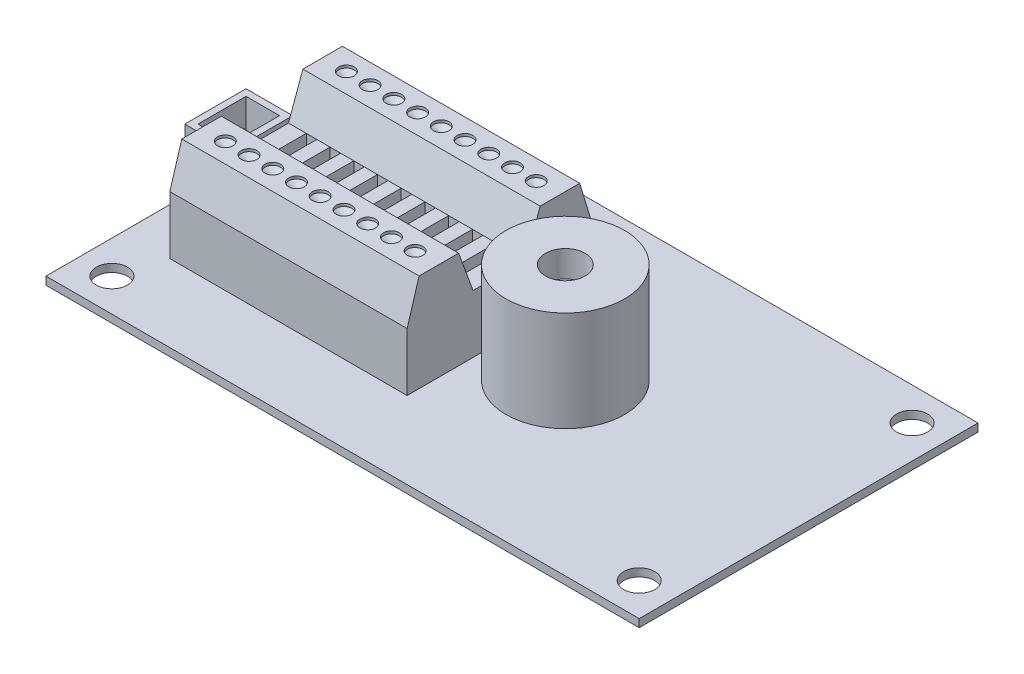
SolidWorks part; units mm, degrees
ref_plane "Front Plane" through (0, 0, 0) normal (0, 0, 1) x (1, 0, 0)
ref_plane "Top Plane" through (0, 0, 0) normal (0, 1, 0) x (1, 0, 0)
ref_plane "Right Plane" through (0, 0, 0) normal (1, 0, 0) x (0, 0, -1)
sketch "Sketch1" plane through (0, 0, 0) normal (0, 1, 0) x (1, 0, 0)
  line L1 (-28.575, 16.3195) -> (28.575, 16.3195)
  line L2 (-28.575, 16.3195) -> (-28.575, -16.3195)
  line L3 (-28.575, -16.3195) -> (28.575, -16.3195)
  line L4 (28.575, 16.3195) -> (28.575, -16.3195)
  line L5 (-28.575, 16.3195) -> (28.575, -16.3195) construction
  line L6 (-28.575, -16.3195) -> (28.575, 16.3195) construction
  point P0 (0, 0)
  dimension "D1" = 32.639
  dimension "D2" = 57.15
extrude "Boss-Extrude1" add sketch "Sketch1" along normal blind 0.762
hole_wizard "Ø3.0mm Dowel Hole1" positions "Sketch2" profile "Sketch3" hole size "Ø3.0" standard "ANSI Metric" end condition through all
sketch "Sketch2" plane through (0, 0.762, 0) normal (0, 1, 0) x (1, 0, 0)
  line L0 (28.575, 16.3195) -> (-28.575, 16.3195) construction
  line L1 (-28.575, 16.3195) -> (-28.575, -16.3195) construction
  line L2 (28.575, -16.3195) -> (28.575, 16.3195) construction
  line L3 (-28.575, -16.3195) -> (28.575, -16.3195) construction
  point P0 (-25.4, 13.1445)
  point P2 (-25.4, -13.1445)
  point P4 (25.4, -13.1445)
  point P6 (25.4, 13.1445)
  point P13 (0, 0)
  dimension "D1" = 3.175
  dimension "D2" = 3.175
  dimension "D3" = 3.175
  dimension "D4" = 3.175
sketch "Sketch3" plane through (-25.4, 0.762, -13.1445) normal (1, 0, 0) x (0, 0, 1)
  line L0 (0, 0) -> (0, 0.762)
  line L1 (0, 0.762) -> (1.5, 0.762)
  line L2 (1.5, 0.762) -> (1.5, 0)
  line L5 (1.5, 0) -> (0, 0)
  line L11 (0, -6.35) -> (0, 107.95) construction
  dimension "Thru Hole Dia." = 3
  dimension "Thru Hole Depth" = 0.762
sketch "Sketch5" plane through (0, 0.762, 0) normal (0, 1, 0) x (1, 0, 0)
  line L0 (-28.575, 16.3195) -> (-28.575, -16.3195) construction
  line L1 (-28.575, 2.95) -> (-24.075, 2.95)
  line L2 (-28.575, 2.95) -> (-28.575, -2.95)
  line L3 (-28.575, -2.95) -> (-24.075, -2.95)
  line L4 (-24.075, 2.95) -> (-24.075, -2.95)
  line L5 (-28.575, 2.95) -> (-24.075, -2.95) construction
  line L6 (-28.575, -2.95) -> (-24.075, 2.95) construction
  point P0 (-26.325, 0)
  point P7 (0, 0)
  dimension "D1" = 5.9
  dimension "D2" = 4.5
  dimension "D3" = 0
extrude "Boss-Extrude2" add sketch "Sketch5" along normal blind 6
sketch "Sketch6" plane through (0, 6.762, 0) normal (0, 1, 0) x (1, 0, 0)
  line L0 (-24.075, 2.95) -> (-28.575, 2.95) construction
  line L1 (-27.94, 2.315) -> (-24.71, 2.315)
  line L2 (-27.94, 2.315) -> (-27.94, -2.315)
  line L3 (-27.94, -2.315) -> (-24.71, -2.315)
  line L4 (-24.71, 2.315) -> (-24.71, -2.315)
  line L5 (-27.94, 2.315) -> (-24.71, -2.315) construction
  line L6 (-27.94, -2.315) -> (-24.71, 2.315) construction
  line L7 (-28.575, -2.95) -> (-24.075, -2.95) construction
  line L8 (-24.075, -2.95) -> (-24.075, 2.95) construction
  line L9 (-28.575, 2.95) -> (-28.575, -2.95) construction
  point P0 (-26.325, 0)
  dimension "D1" = 0.635
  dimension "D2" = 0.635
  dimension "D3" = 0.635
  dimension "D4" = 0.635
extrude "Cut-Extrude1" cut sketch "Sketch6" against normal blind 5.08
sketch "Sketch7" plane through (0, 1.682, 0) normal (0, 1, 0) x (1, 0, 0)
  line L0 (-28.575, 2.95) -> (-28.575, -2.95) construction
  line L3 (-24.075, 2.95) -> (-28.575, 2.95) construction
  line L4 (-28.575, -2.95) -> (-24.075, -2.95) construction
  circle A0 centre (-26.875, 1) radius 0.25
  circle A1 centre (-26.875, -1) radius 0.25
  point P8 (0, 0)
  point P11 (0, 0)
  dimension "D1" = 0.5
  dimension "D2" = 0.5
  dimension "D3" = 2
  dimension "D5" = 1.95
  dimension "D6" = 1.95
  dimension "D4" = 1.7
extrude "Boss-Extrude3" add sketch "Sketch7" along normal blind 3.4
ref_plane "Plane1" through (-24.075, 0, 0) normal (1, 0, 0) x (0, 0, -1)
sketch "Sketch9" plane through (-24.075, 0, 0) normal (1, 0, 0) x (0, 0, -1)
  line L0 (0, 0) -> (0, 6.35)
  line L1 (0, 6.35) -> (2.54, 6.35)
  line L2 (2.54, 6.35) -> (3.9267, 10.16)
  line L3 (3.9267, 10.16) -> (7.7367, 10.16)
  line L4 (7.7367, 10.16) -> (8.89, 6.35)
  line L5 (8.89, 6.35) -> (8.89, 0)
  line L6 (8.89, 0) -> (0, 0)
  dimension "D1" = 10.16
  dimension "D2" = 3.81
  dimension "D3" = 8.89
  dimension "D4" = 6.35
  dimension "D5" = 110
  dimension "D6" = 2.54
extrude "Boss-Extrude4" add sketch "Sketch9" along normal blind 22.86
hole_wizard "Ø1.5mm Dowel Hole1" positions "Sketch12" profile "Sketch11" hole size "Ø1.5" standard "ANSI Metric"
sketch "Sketch12" plane through (0, 10.16, 0) normal (0, 1, 0) x (1, 0, 0)
  line L0 (-24.075, 8.89) -> (-24.075, 2.95) construction
  line L1 (-1.215, 7.7367) -> (-24.075, 7.7367) construction
  point P0 (-21.789, 5.8317)
  point P2 (-19.503, 5.8317)
  point P4 (-17.217, 5.8317)
  point P6 (-14.931, 5.8317)
  point P8 (-12.645, 5.8317)
  point P10 (-10.359, 5.8317)
  point P12 (-8.073, 5.8317)
  point P14 (-5.787, 5.8317)
  point P16 (-3.501, 5.8317)
  point P21 (0, 0)
  dimension "D1" = 2.286
  dimension "D2" = 2.286
  dimension "D3" = 2.286
  dimension "D4" = 2.286
  dimension "D5" = 2.286
  dimension "D6" = 2.286
  dimension "D7" = 2.286
  dimension "D8" = 2.286
  dimension "D9" = 2.286
  dimension "D10" = 1.905
sketch "Sketch11" plane through (-21.789, 10.16, -5.8317) normal (1, 0, 0) x (0, 0, 1)
  line L0 (0, 0) -> (0, 0.7046)
  line L1 (0, 0.7046) -> (0.75, 0.254)
  line L2 (0.75, 0.254) -> (0.75, 0)
  line L5 (0.75, 0) -> (0, 0)
  line L10 (0, 0.7046) -> (-0.75, 0.254) construction
  line L11 (0, -6.35) -> (0, 107.95) construction
  dimension "Hole Dia." = 1.5
  dimension "Hole Depth" = 0.254
  dimension "Drill Angle" = 118
sketch "Sketch13" plane through (0, 6.35, 0) normal (0, 1, 0) x (1, 0, 0)
  line L0 (-1.215, 2.54) -> (-24.075, 2.54) construction
  line L1 (-22.3558, 2.54) -> (-21.3398, 2.54)
  line L2 (-22.3558, 2.54) -> (-22.3558, 0)
  line L3 (-22.3558, 0) -> (-21.3398, 0)
  line L4 (-21.3398, 2.54) -> (-21.3398, 0)
  line L5 (-1.215, 0) -> (-24.075, 0) construction
  dimension "D1" = 1.016
extrude "Cut-Extrude2" cut sketch "Sketch13" against normal blind 1.27
pattern_linear "LPattern1" count 9 spacing 2.286 along (1, 0, 0) of "Cut-Extrude2"
mirror "Mirror1" about plane through (0, 0, 0) normal (0, 0, 1) of "LPattern1", "Cut-Extrude2", "Boss-Extrude4", "Ø1.5mm Dowel Hole1"
sketch "Sketch15" plane through (0, 0.762, 0) normal (0, 1, 0) x (1, 0, 0)
  line L0 (-1.215, 8.89) -> (-1.215, -8.89) construction
  circle A0 centre (5.135, 0) radius 5.715
  point P2 (0, 0)
  dimension "D1" = 11.43
  dimension "D2" = 6.35
extrude "Boss-Extrude5" add sketch "Sketch15" along normal blind 9.652
sketch "Sketch16" plane through (0, 10.414, 0) normal (0, 1, 0) x (1, 0, 0)
  circle A0 centre (5.135, 0) radius 1.905
  circle A1 centre (5.135, 0) radius 5.715 construction
  dimension "D1" = 3.81
extrude "Cut-Extrude3" cut sketch "Sketch16" against normal blind 2.54
